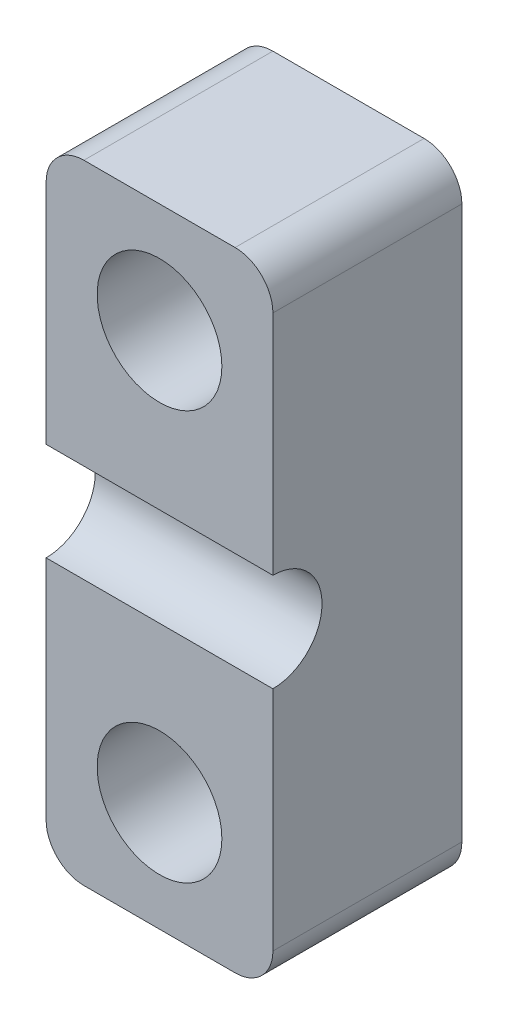
SolidWorks part; units mm, degrees
ref_plane "Front Plane" through (0, 0, 0) normal (0, 0, 1) x (1, 0, 0)
ref_plane "Top Plane" through (0, 0, 0) normal (0, 1, 0) x (1, 0, 0)
ref_plane "Right Plane" through (0, 0, 0) normal (1, 0, 0) x (0, 0, -1)
sketch "Sketch1" plane through (0, 0, 0) normal (0, 0, 1) x (1, 0, 0)
  line L0 (-2, -8.31) -> (2, -8.31)
  line L1 (-3, -7.31) -> (-3, 7.31)
  line L2 (-2, 8.31) -> (2, 8.31)
  line L3 (3, -7.31) -> (3, 7.31)
  circle A0 centre (0, -5.41) radius 1.65
  circle A1 centre (0, 5.41) radius 1.65
  arc A2 (-3, 7.31) -> (-2, 8.31) centre (-2, 7.31) cw
  arc A3 (2, 8.31) -> (3, 7.31) centre (2, 7.31) cw
  arc A4 (2, -8.31) -> (3, -7.31) centre (2, -7.31) ccw
  arc A5 (-2, -8.31) -> (-3, -7.31) centre (-2, -7.31) cw
extrude "Boss-Extrude1" add sketch "Sketch1" along normal blind 5
sketch "Sketch2" plane through (3, 0, 0) normal (1, 0, 0) x (0, 0, -1)
  line L1 (-5, -1.3) -> (-5, 1.3)
  arc A0 (-5, -1.3) -> (-5, 1.3) centre (-5, 0) ccw
extrude "Cut-Extrude1" cut sketch "Sketch2" against normal up to surface (6 mm away) up to face at (-3, 0, 2.5)
